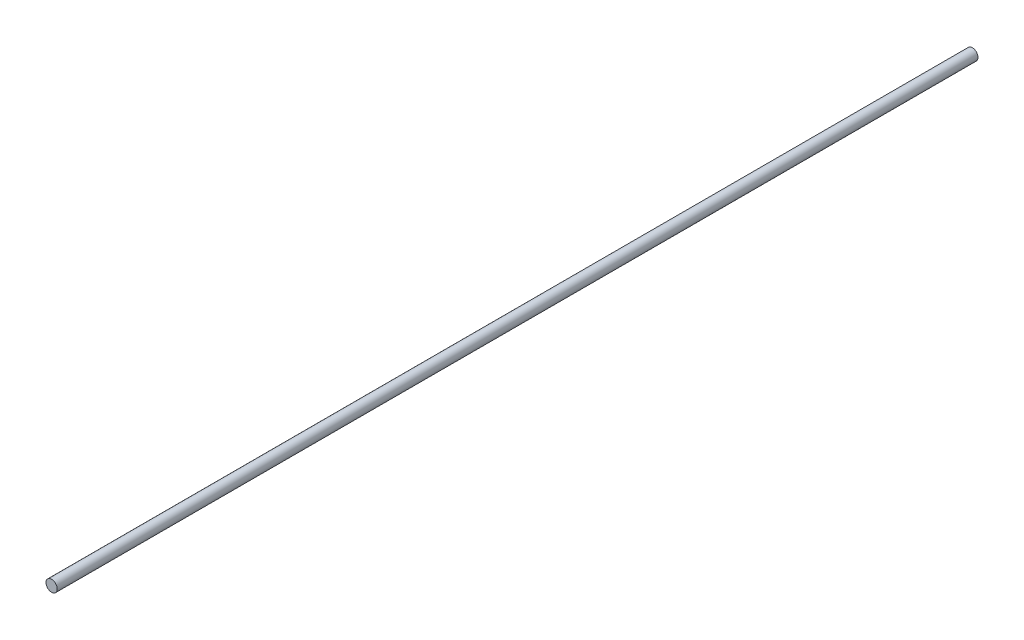
SolidWorks part; units mm, degrees
material "Alloy Steel"
ref_plane "Front Plane" through (0, 0, 0) normal (0, 0, 1) x (1, 0, 0)
ref_plane "Top Plane" through (0, 0, 0) normal (0, 1, 0) x (1, 0, 0)
ref_plane "Right Plane" through (0, 0, 0) normal (1, 0, 0) x (0, 0, -1)
sketch "Sketch1" plane through (0, 0, 0) normal (0, 0, 1) x (1, 0, 0)
  circle A0 centre (0, 0) radius 4
  dimension "D1" = 8
extrude "Boss-Extrude1" add sketch "Sketch1" against normal blind 655
